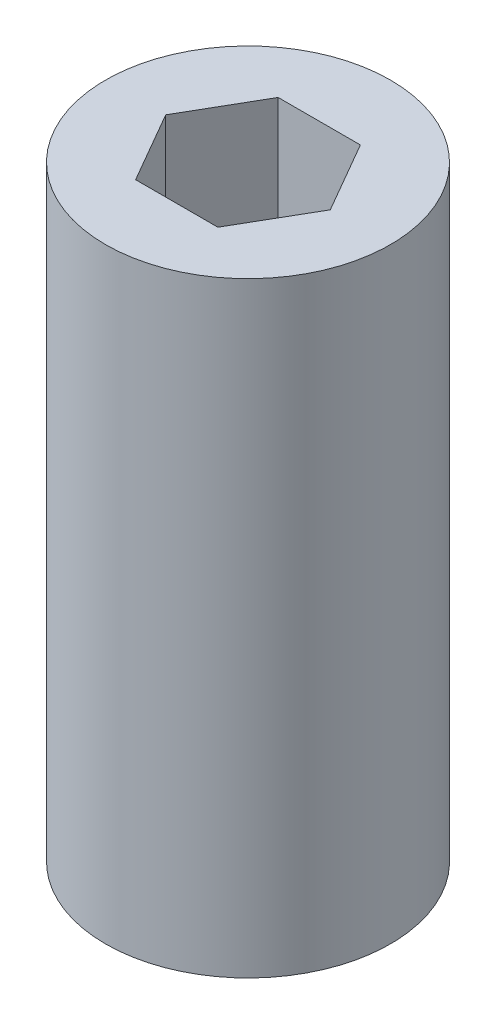
SolidWorks part; units mm, degrees
ref_plane "Front Plane" through (0, 0, 0) normal (0, 0, 1) x (1, 0, 0)
ref_plane "Top Plane" through (0, 0, 0) normal (0, 1, 0) x (1, 0, 0)
ref_plane "Right Plane" through (0, 0, 0) normal (1, 0, 0) x (0, 0, -1)
sketch "Sketch1" plane through (0, 0, 0) normal (0, 1, 0) x (1, 0, 0)
  line L1 (3.6662, -6.35) -> (7.3323, 0)
  line L2 (7.3323, 0) -> (3.6662, 6.35)
  line L3 (3.6662, 6.35) -> (-3.6662, 6.35)
  line L4 (-3.6662, 6.35) -> (-7.3323, 0)
  line L5 (-7.3323, 0) -> (-3.6662, -6.35)
  line L6 (-3.6662, -6.35) -> (3.6662, -6.35)
  circle A0 centre (0, 0) radius 6.35 construction
  circle A1 centre (0, 0) radius 12.7
  dimension "D2" = 25.4
  dimension "D1" = 12.7
extrude "Boss-Extrude1" add sketch "Sketch1" along normal blind 53.975
